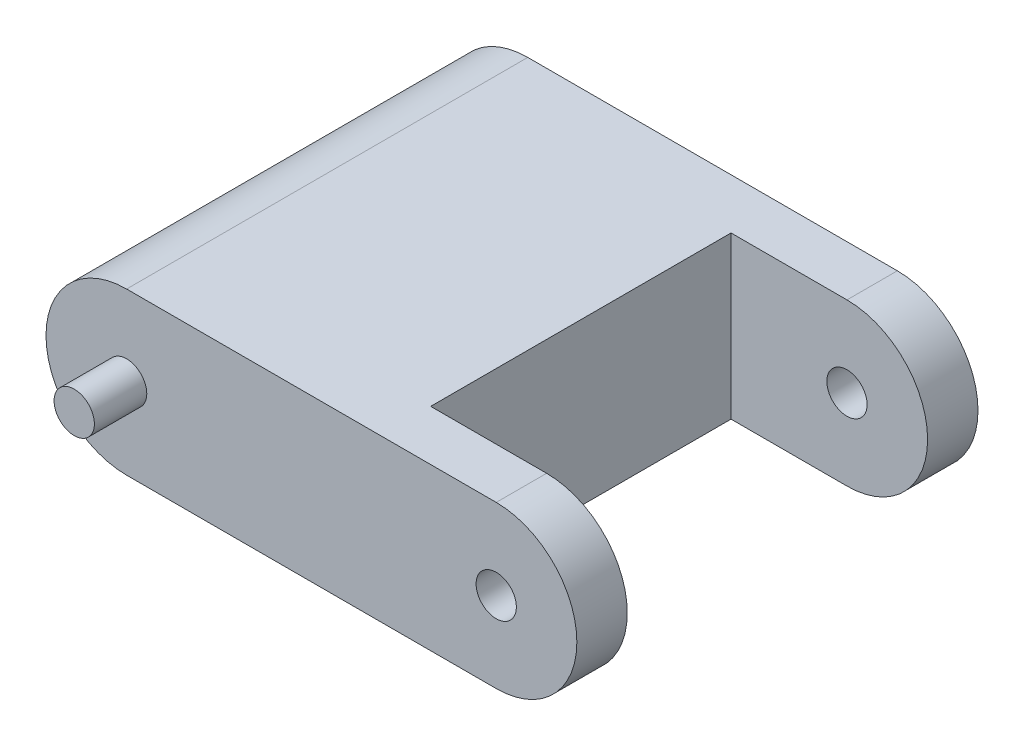
SolidWorks part; units mm, degrees
ref_plane "Alzado" through (0, 0, 0) normal (0, 0, 1) x (1, 0, 0)
ref_plane "Planta" through (0, 0, 0) normal (0, 1, 0) x (1, 0, 0)
ref_plane "Vista lateral" through (0, 0, 0) normal (1, 0, 0) x (0, 0, -1)
sketch "Croquis2" plane through (0, 0, 0) normal (0, 0, 1) x (1, 0, 0)
  line L0 (0, 40) -> (183.352, 40)
  line L1 (0, -40) -> (183.352, -40)
  arc A0 (0, 40) -> (0, -40) centre (0, 0) ccw
  arc A1 (183.352, -40) -> (183.352, 40) centre (183.352, 0) ccw
  dimension "D2" = 80
extrude "Saliente-Extruir1" add sketch "Croquis2" along normal blind 199
sketch "Croquis3" plane through (0, 0, 199) normal (0, 0, 1) x (1, 0, 0)
  circle A0 centre (0, 0) radius 10
sketch "Croquis6" plane through (0, 0, 0) normal (0, 0, -1) x (-1, 0, 0)
  circle A2 centre (-183.352, 0) radius 9.988
extrude "Cortar-Extruir3" cut sketch "Croquis6" against normal blind 240
sketch "Croquis10" plane through (0, 40, 0) normal (0, 1, 0) x (1, 0, 0)
  line L0 (223.352, -199) -> (223.352, 0) construction
  line L1 (223.352, -25) -> (124.5702, -25)
  line L2 (223.352, -25) -> (223.352, -174)
  line L3 (223.352, -174) -> (124.5702, -174)
  line L4 (124.5702, -25) -> (124.5702, -174)
  dimension "D1" = 25
  dimension "D2" = 25
extrude "Cortar-Extruir5" [suppressed] cut sketch "Croquis10" against normal blind 240
extrude "Saliente-Extruir3" add sketch "Croquis3" along normal blind 26 and the other way blind 225
sketch "Croquis12" plane through (0, 40, 0) normal (0, 1, 0) x (1, 0, 0)
  line L1 (249.4821, -25) -> (125.8352, -25)
  line L2 (249.4821, -25) -> (249.4821, -174)
  line L3 (249.4821, -174) -> (125.8352, -174)
  line L4 (125.8352, -25) -> (125.8352, -174)
  dimension "D1" = 25
  dimension "D2" = 25
  dimension "D3" = 149
extrude "Cortar-Extruir7" cut sketch "Croquis12" against normal blind 122
